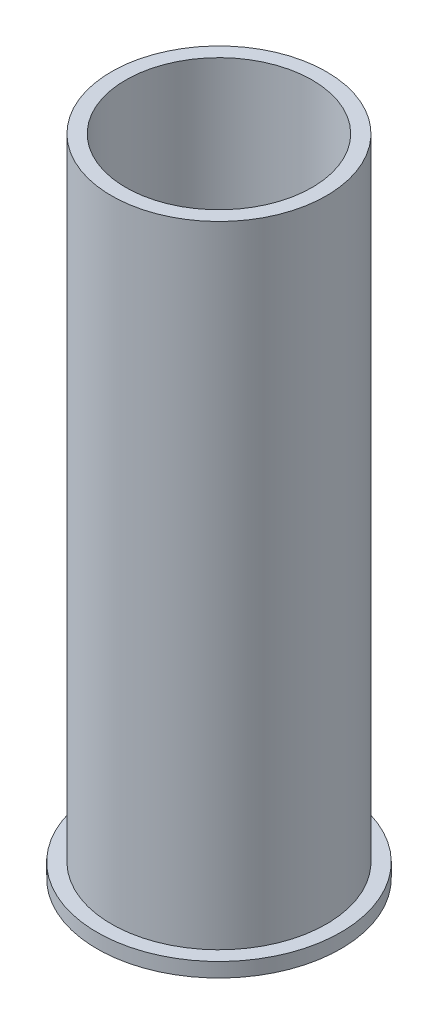
SolidWorks part; units mm, degrees
material "AISI 304"
ref_plane "前视基准面" through (0, 0, 0) normal (0, 0, 1) x (1, 0, 0)
ref_plane "上视基准面" through (0, 0, 0) normal (0, 1, 0) x (1, 0, 0)
ref_plane "右视基准面" through (0, 0, 0) normal (1, 0, 0) x (0, 0, -1)
sketch "Sketch1" plane through (0, 0, 0) normal (0, 0, 1) x (1, 0, 0)
  line L0 (32.5, -163.861) -> (32.5, 61.139)
  line L5 (37.5, 61.139) -> (37.5, -158.861)
  line L6 (37.5, -163.861) -> (32.5, -163.861)
  line L7 (0, 0) -> (0, 76.2307) construction
  line L11 (37.5, -163.861) -> (42.5, -163.861)
  line L12 (42.5, -163.861) -> (42.5, -158.861)
  line L13 (42.5, -158.861) -> (37.5, -158.861)
  line L14 (32.5, 61.139) -> (37.5, 61.139)
  point P15 (40, -163.861)
  dimension "D1" = 65
  dimension "D2" = 220
  dimension "D4" = 225
  dimension "D5" = 5
revolve "Revolve1" add sketch "Sketch1" angle 360 about L7
